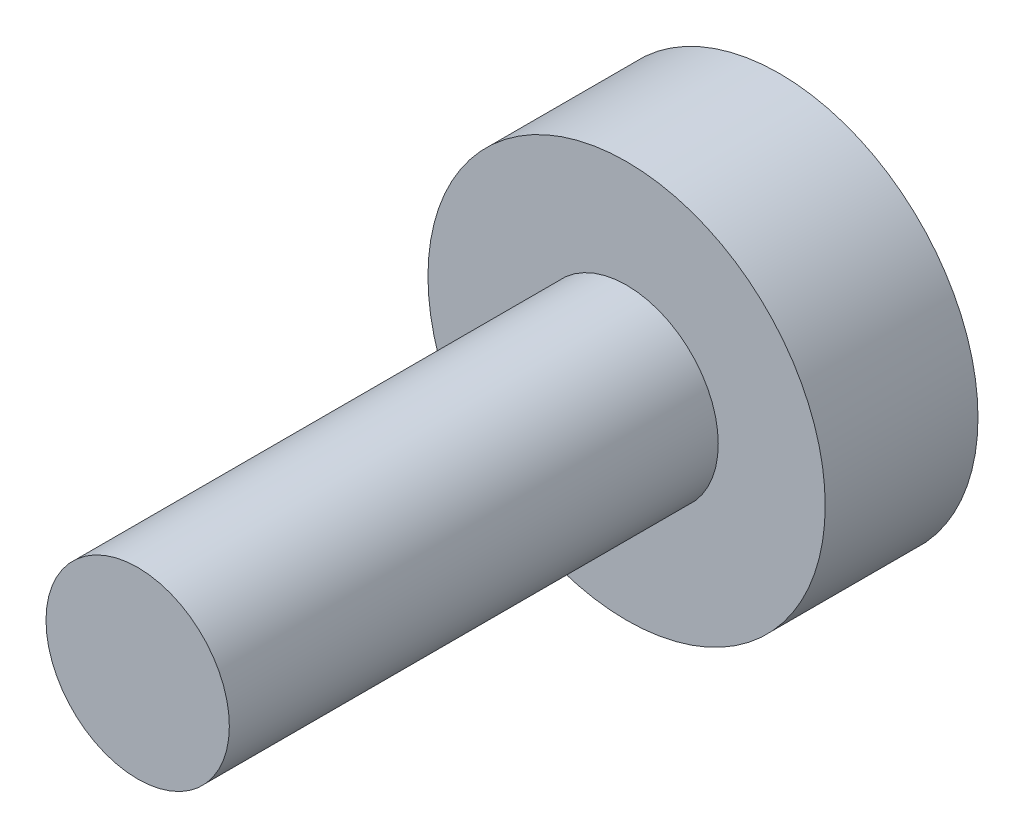
SolidWorks part; units mm, degrees
ref_plane "前视基准面" through (0, 0, 0) normal (0, 0, 1) x (1, 0, 0)
ref_plane "上视基准面" through (0, 0, 0) normal (0, 1, 0) x (1, 0, 0)
ref_plane "右视基准面" through (0, 0, 0) normal (1, 0, 0) x (0, 0, -1)
other "Configuration Table"
sketch "草图1" plane through (0, 0, 0) normal (0, 0, 1) x (1, 0, 0)
  circle A0 centre (0, 0) radius 6.5
extrude "凸台-拉伸1" add sketch "草图1" along normal blind 5 flip side to cut
sketch "草图2" plane through (0, 0, 0) normal (0, 0, 1) x (1, 0, 0)
  circle A0 centre (0, 0) radius 3
extrude "凸台-拉伸2" add sketch "草图2" along normal blind 21 flip side to cut
